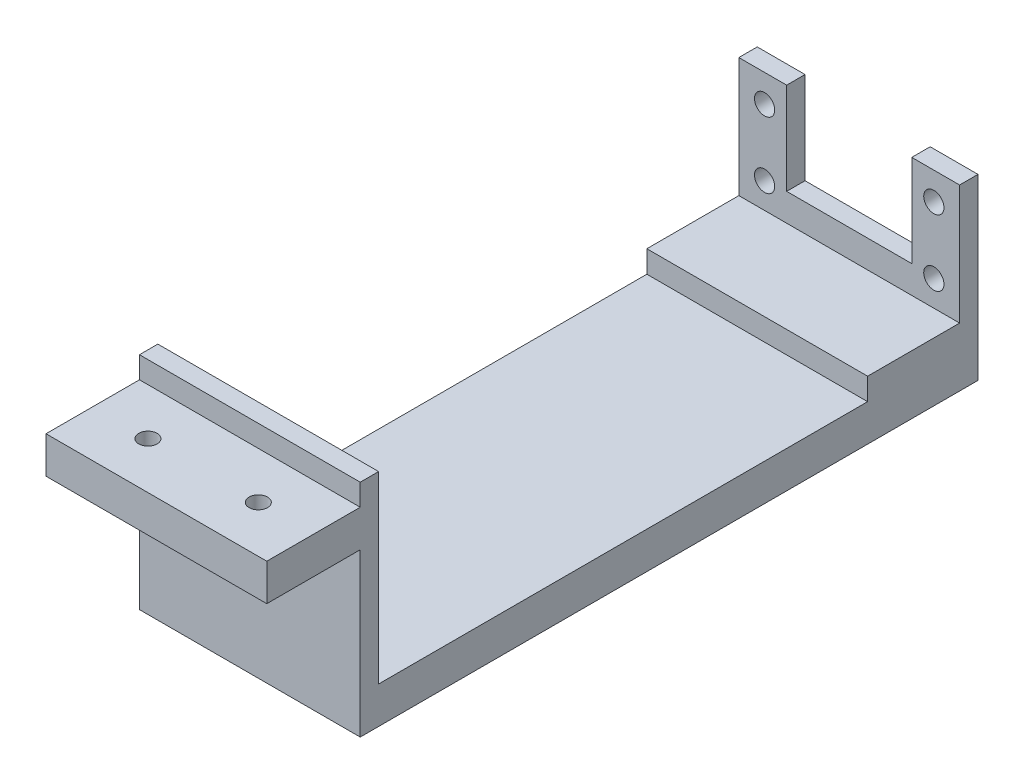
SolidWorks part; units mm, degrees
material "ABS"
ref_plane "Front Plane" through (0, 0, 0) normal (0, 0, 1) x (1, 0, 0)
ref_plane "Top Plane" through (0, 0, 0) normal (0, 1, 0) x (1, 0, 0)
ref_plane "Right Plane" through (0, 0, 0) normal (1, 0, 0) x (0, 0, -1)
sketch "Sketch1" plane through (0, 0, 0) normal (0, 0, 1) x (1, 0, 0)
  line L0 (13, 32.5) -> (13, 7.5)
  line L1 (0, 0) -> (60, 0)
  line L2 (0, 0) -> (0, 32.5)
  line L3 (0, 32.5) -> (60, 32.5)
  line L4 (60, 0) -> (60, 32.5)
  line L5 (13, 7.5) -> (47, 7.5)
  line L6 (47, 7.5) -> (47, 32.5)
  line L7 (30, 32.5) -> (30, 0) construction
  circle A0 centre (7, 25) radius 2.75
  circle A1 centre (7, 7) radius 2.75
  circle A2 centre (53, 7) radius 2.75
  circle A3 centre (53, 25) radius 2.75
  point P15 (0, 0)
  dimension "D6" = 5.5
  dimension "D7" = 46
  dimension "D8" = 34
  dimension "D1" = 32.5
  dimension "D2" = 60
  dimension "D3" = 17
  dimension "D4" = 18
  dimension "D5" = 25
  dimension "D9" = 25
extrude "Boss-Extrude1" add sketch "Sketch1" along normal blind 5 contours L7 L5 L0 L3 L2 L1 A1 A0 | L5 L7 L1 L4 L3 L6 A3 A2
sketch "Sketch2" plane through (0, 0, 5) normal (0, 0, 1) x (1, 0, 0)
  line L0 (60, 0) -> (60, 32.5) construction
  line L1 (0, 0) -> (60, 0)
  line L2 (0, 0) -> (0, -6)
  line L3 (0, -6) -> (60, -6)
  line L4 (60, 0) -> (60, -6)
  dimension "D1" = 6
extrude "Boss-Extrude2" add sketch "Sketch2" along normal blind 25 and the other way blind 5
sketch "Sketch3" plane through (0, 0, 0) normal (0, 0, -1) x (-1, 0, 0)
  line L0 (0, -6) -> (0, 32.5) construction
  line L1 (-60, -6) -> (0, -6)
  line L2 (-60, -6) -> (-60, -16)
  line L3 (-60, -16) -> (0, -16)
  line L4 (0, -6) -> (0, -16)
  dimension "D1" = 10
extrude "Boss-Extrude3" add sketch "Sketch3" against normal blind 167.8942
sketch "Sketch4" plane through (0, -6, 0) normal (0, 1, 0) x (1, 0, 0)
  line L0 (60, -167.8942) -> (60, -30) construction
  line L1 (0, -167.8942) -> (60, -167.8942)
  line L2 (0, -167.8942) -> (0, -162.8942)
  line L3 (0, -162.8942) -> (60, -162.8942)
  line L4 (60, -167.8942) -> (60, -162.8942)
  dimension "D1" = 5
extrude "Boss-Extrude4" add sketch "Sketch4" along normal blind 50
sketch "Sketch5" plane through (0, 0, 167.8942) normal (0, 0, 1) x (1, 0, 0)
  line L0 (0, -16) -> (0, 44) construction
  line L1 (0, 28.0996) -> (60, 28.0996)
  line L2 (0, 28.0996) -> (0, 38.0996)
  line L3 (0, 38.0996) -> (60, 38.0996)
  line L4 (60, 28.0996) -> (60, 38.0996)
  line L5 (60, 44) -> (60, -16) construction
  line L7 (0, 44) -> (60, 44) construction
  dimension "D1" = 15.9004
  dimension "D2" = 10
extrude "Boss-Extrude5" add sketch "Sketch5" along normal blind 25.4
sketch "Sketch6" plane through (0, 38.0996, 0) normal (0, 1, 0) x (1, 0, 0)
  line L0 (0, -180.5942) -> (30, -180.5942) construction
  line L1 (30, -193.2942) -> (30, -167.8942) construction
  line L2 (60, -180.5942) -> (30, -180.5942) construction
  line L4 (60, -167.8942) -> (0, -167.8942)
  line L5 (0, -167.8942) -> (0, -193.2942)
  line L6 (0, -193.2942) -> (60, -193.2942)
  line L7 (60, -193.2942) -> (60, -167.8942)
  line L8 (60, -167.8942) -> (0, -167.8942)
  line L9 (0, -167.8942) -> (0, -193.2942)
  line L10 (0, -193.2942) -> (60, -193.2942)
  line L11 (60, -193.2942) -> (60, -167.8942)
  point P1 (0, -167.8942)
  point P4 (15, -180.5942)
  point P10 (45, -180.5942)
  dimension "D1" = 0
hole_wizard "M5x0.8 Tapped Hole1" positions "Sketch6" profile "Sketch7" tap size "M5x0.8" standard "ANSI Metric"
sketch "Sketch7" plane through (45, 38.0996, 180.5942) normal (1, 0, 0) x (0, 0, 1)
  line L0 (0, 0) -> (0, 54.0996)
  line L1 (0, 54.0996) -> (2.5, 54.0996)
  line L2 (2.5, 54.0996) -> (2.5, 0)
  line L5 (2.5, 0) -> (0, 0)
  line L11 (0, -6.35) -> (0, 107.95) construction
  dimension "Thread Major Dia." = 5
  dimension "Thru Tap Drill Depth" = 54.0996
